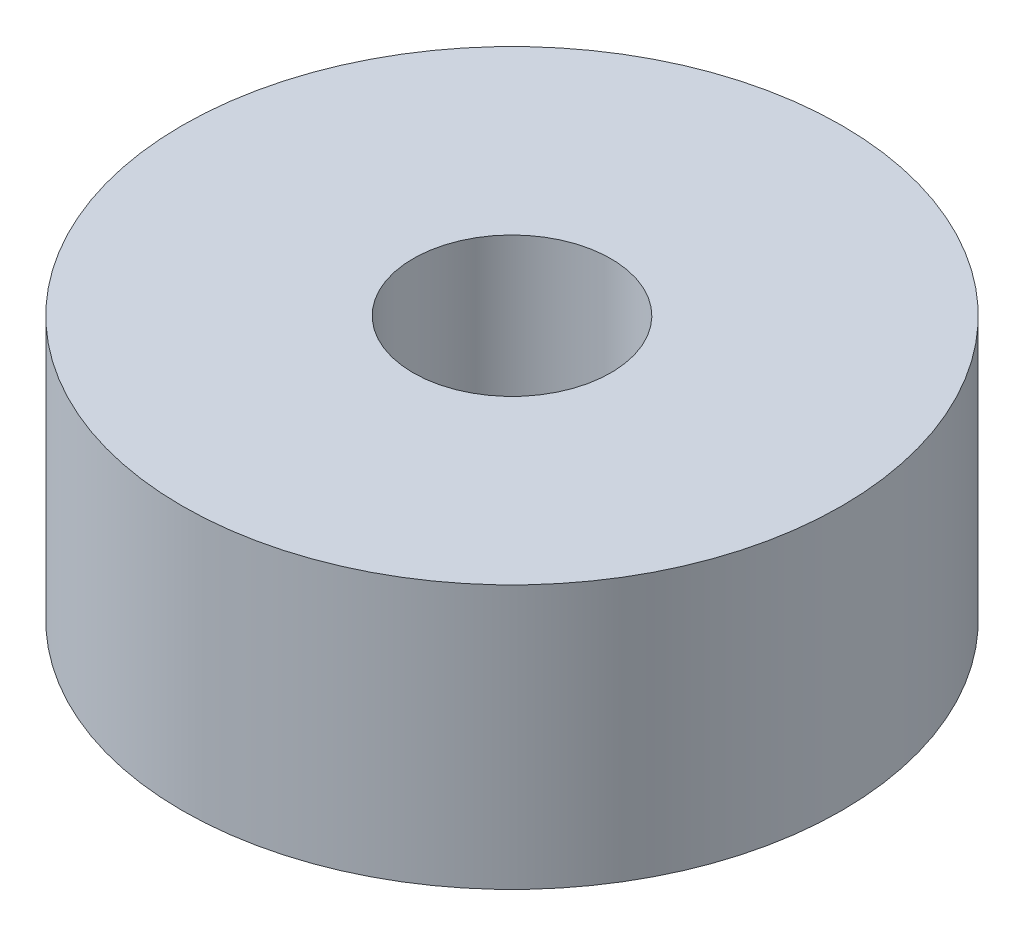
SolidWorks part; units mm, degrees
ref_plane "前视基准面" through (0, 0, 0) normal (0, 0, 1) x (1, 0, 0)
ref_plane "上视基准面" through (0, 0, 0) normal (0, 1, 0) x (1, 0, 0)
ref_plane "右视基准面" through (0, 0, 0) normal (1, 0, 0) x (0, 0, -1)
sketch "草图1" plane through (0, 0, 0) normal (0, 1, 0) x (1, 0, 0)
  circle A0 centre (0, 0) radius 5
  circle A1 centre (0, 0) radius 1.5
  dimension "D1" = 3
  dimension "D2" = 10
extrude "凸台-拉伸1" add sketch "草图1" along normal blind 4
